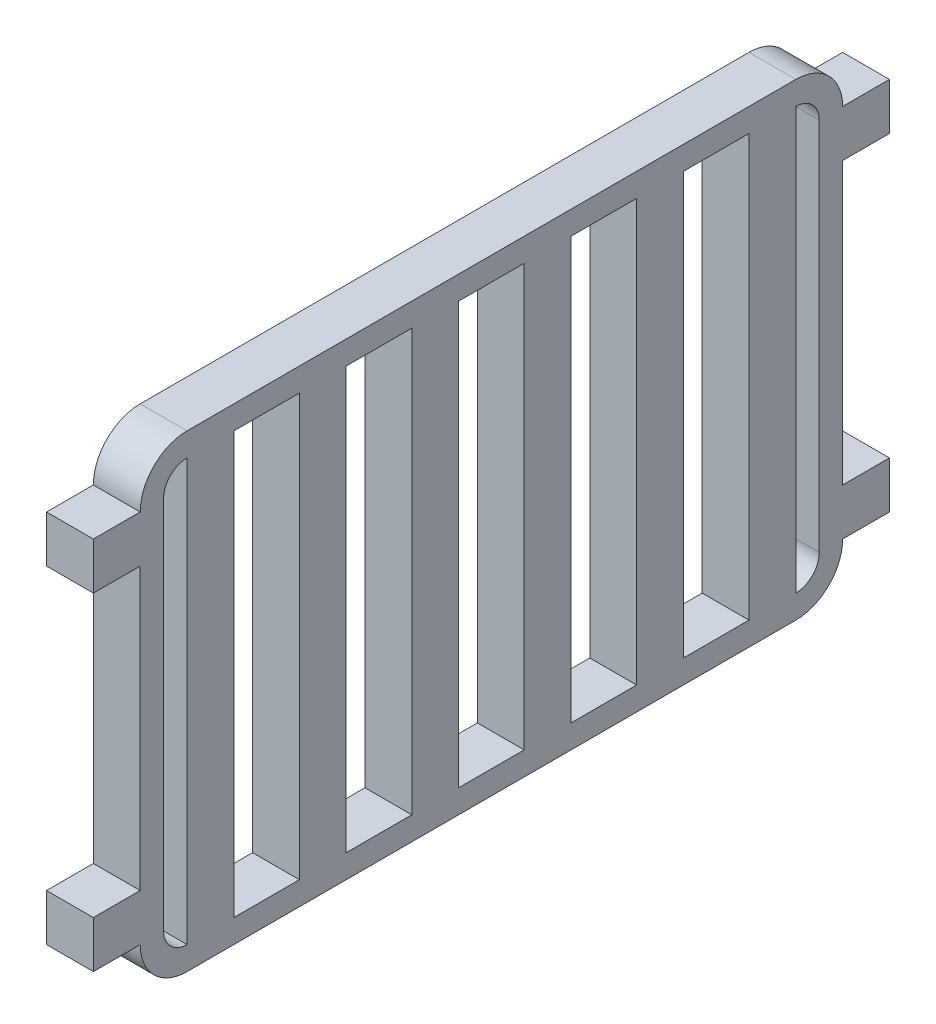
SolidWorks part; units mm, degrees
ref_plane "Front Plane" through (0, 0, 0) normal (0, 0, 1) x (1, 0, 0)
ref_plane "Top Plane" through (0, 0, 0) normal (0, 1, 0) x (1, 0, 0)
ref_plane "Right Plane" through (0, 0, 0) normal (1, 0, 0) x (0, 0, -1)
sketch "Sketch1" plane through (0, 0, 0) normal (1, 0, 0) x (0, 0, -1)
  line L0 (-75, 25) -> (-90, 25)
  line L1 (-65, 50) -> (65, 50)
  line L2 (-75, 40) -> (-75, -40)
  line L3 (-65, -50) -> (65, -50)
  line L4 (75, 40) -> (75, -40)
  line L5 (-65, 45) -> (65, 45)
  line L6 (70, 40) -> (70, -40)
  line L7 (-90, 25) -> (-90, -25)
  line L8 (-90, -25) -> (-75, -25)
  line L9 (-65, -45) -> (65, -45)
  line L10 (-70, 40) -> (-70, -40)
  line L11 (90, -25) -> (75, -25)
  line L12 (75, 25) -> (90, 25)
  line L13 (90, 25) -> (90, -25)
  line L14 (75, 20) -> (85, 20)
  line L15 (85, 20) -> (85, -20)
  line L16 (-75, 20) -> (-85, 20)
  line L17 (-85, 20) -> (-85, -20)
  line L18 (-85, -20) -> (-75, -20)
  line L19 (85, -20) -> (75, -20)
  arc A0 (65, -50) -> (75, -40) centre (65, -40) ccw
  arc A1 (-65, -50) -> (-75, -40) centre (-65, -40) cw
  arc A2 (75, 40) -> (65, 50) centre (65, 40) ccw
  arc A3 (-75, 40) -> (-65, 50) centre (-65, 40) cw
  arc A4 (70, 40) -> (65, 45) centre (65, 40) ccw
  arc A5 (65, -45) -> (70, -40) centre (65, -40) ccw
  arc A6 (-65, -45) -> (-70, -40) centre (-65, -40) cw
  arc A7 (-70, 40) -> (-65, 45) centre (-65, 40) cw
  point P0 (0, 0)
  point P42 (0, 0)
  dimension "D3" = 10
  dimension "D1" = 5
  dimension "D2" = 5
  dimension "D4" = 50
  dimension "D5" = 15
  dimension "D6" = 5
extrude "Boss-Extrude2" add sketch "Sketch1" along normal blind 10 contours L1 A2 L4 A0 L3 A1 L2 A3
sketch "Sketch2" plane through (10, 0, 0) normal (1, 0, 0) x (0, 0, -1)
  line L8 (-70, 40) -> (-70, -40)
  line L9 (-65, -45) -> (65, -45)
  line L10 (70, -40) -> (70, 40)
  line L11 (65, 45) -> (-65, 45)
  line L12 (-70, 40) -> (-70, -40)
  line L13 (-65, -45) -> (65, -45)
  line L14 (70, -40) -> (70, 40)
  line L15 (65, 45) -> (-65, 45)
  arc A8 (-65, 45) -> (-70, 40) centre (-65, 40) ccw
  arc A9 (-70, -40) -> (-65, -45) centre (-65, -40) ccw
  arc A10 (65, -45) -> (70, -40) centre (65, -40) ccw
  arc A11 (70, 40) -> (65, 45) centre (65, 40) ccw
  arc A12 (-65, 45) -> (-70, 40) centre (-65, 40) ccw
  arc A13 (-70, -40) -> (-65, -45) centre (-65, -40) ccw
  arc A14 (65, -45) -> (70, -40) centre (65, -40) ccw
  arc A15 (70, 40) -> (65, 45) centre (65, 40) ccw
  dimension "D1" = 5
extrude "Cut-Extrude1" cut sketch "Sketch2" against normal blind 10
sketch "Sketch3" plane through (0, 0, 75) normal (0, 0, 1) x (1, 0, 0)
  line L0 (10, 40) -> (10, -40) construction
  line L1 (0, 40) -> (10, 40)
  line L2 (0, 40) -> (0, 30)
  line L3 (0, 30) -> (10, 30)
  line L4 (10, 40) -> (10, 30)
  line L5 (10, 0) -> (0, 0) construction
  line L6 (10, -40) -> (10, -30)
  line L7 (0, -40) -> (10, -40)
  line L8 (0, -40) -> (0, -30)
  line L9 (0, -30) -> (10, -30)
  dimension "D1" = 10
extrude "Boss-Extrude4" add sketch "Sketch3" along normal blind 10
sketch "Sketch4" plane through (0, 0, -75) normal (0, 0, -1) x (-1, 0, 0)
  line L0 (0, 40) -> (0, -40) construction
  line L1 (-10, 40) -> (0, 40)
  line L2 (-10, 40) -> (-10, 30)
  line L3 (-10, 30) -> (0, 30)
  line L4 (0, 40) -> (0, 30)
  line L5 (-10, 0) -> (0, 0) construction
  line L6 (-10, 40) -> (-10, -40) construction
  line L7 (-10, -40) -> (0, -40)
  line L8 (0, -40) -> (0, -30)
  line L9 (-10, -30) -> (0, -30)
  line L10 (-10, -40) -> (-10, -30)
  dimension "D1" = 10
extrude "Boss-Extrude5" add sketch "Sketch4" along normal blind 10
sketch "Sketch6" plane through (0, -45, 0) normal (0, 1, 0) x (1, 0, 0)
  line L0 (10, -65) -> (10, 65) construction
  line L1 (0, 65) -> (10, 65)
  line L2 (0, 65) -> (0, 55)
  line L3 (0, 55) -> (10, 55)
  line L4 (10, 65) -> (10, 55)
  line L5 (0, -65) -> (0, 65) construction
  line L7 (0, 41) -> (10, 41)
  line L8 (0, 41) -> (0, 31)
  line L9 (0, 31) -> (10, 31)
  line L10 (10, 41) -> (10, 31)
  line L11 (0, 17) -> (10, 17)
  line L12 (0, 17) -> (0, 7)
  line L13 (0, 7) -> (10, 7)
  line L14 (10, 17) -> (10, 7)
  line L15 (0, -7) -> (10, -7)
  line L16 (0, -7) -> (0, -17)
  line L17 (0, -17) -> (10, -17)
  line L18 (10, -7) -> (10, -17)
  line L23 (0, -55) -> (10, -55)
  line L24 (0, -55) -> (0, -65)
  line L25 (0, -65) -> (10, -65)
  line L26 (10, -55) -> (10, -65)
  line L27 (0, -31) -> (10, -31)
  line L28 (0, -31) -> (0, -41)
  line L29 (0, -41) -> (10, -41)
  line L30 (10, -31) -> (10, -41)
  dimension "D1" = 10
  dimension "D2" = 10
  dimension "D3" = 10
  dimension "D4" = 10
  dimension "D5" = 10
  dimension "D6" = 10
  dimension "D7" = 14
  dimension "D8" = 14
  dimension "D9" = 14
  dimension "D10" = 14
  dimension "D11" = 0
extrude "Boss-Extrude6" add sketch "Sketch6" along normal up to surface (90 mm away) up to face at (5, 45, 0)
